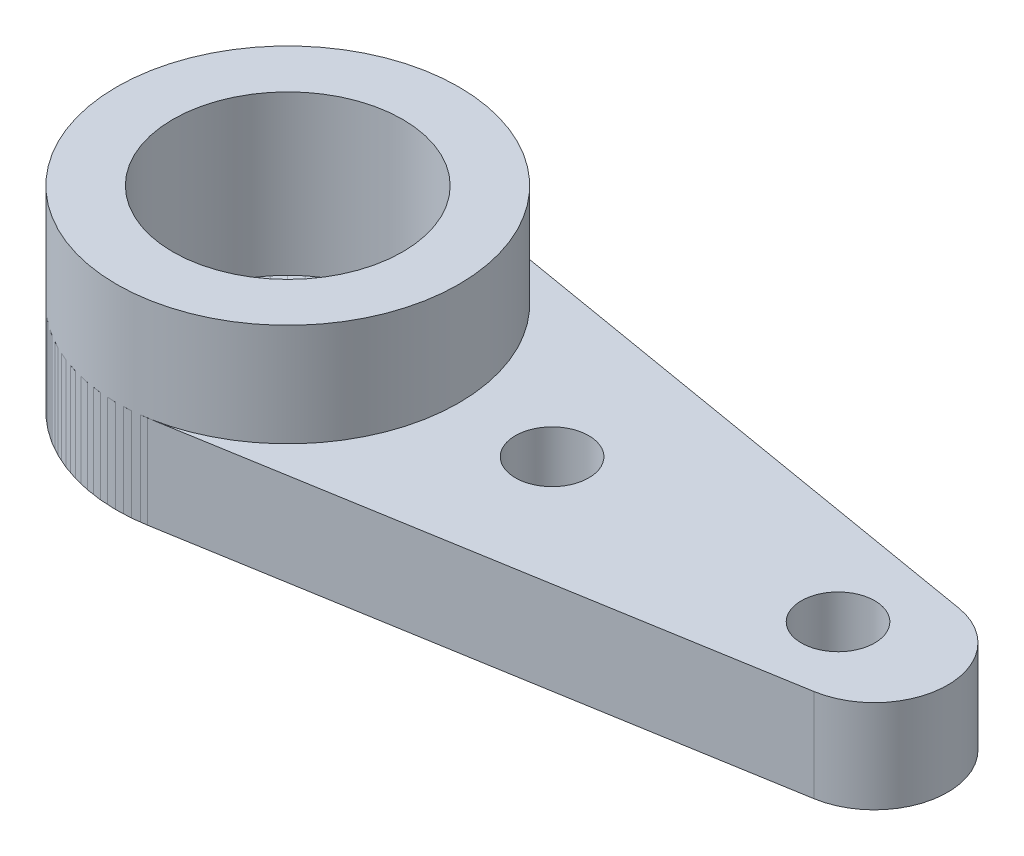
SolidWorks part; units mm, degrees
ref_plane "Front Plane" through (0, 0, 0) normal (0, 0, 1) x (1, 0, 0)
ref_plane "Top Plane" through (0, 0, 0) normal (0, 1, 0) x (1, 0, 0)
ref_plane "Right Plane" through (0, 0, 0) normal (1, 0, 0) x (0, 0, -1)
sketch "Sketch1" plane through (0, 0, 0) normal (0, 1, 0) x (1, 0, 0)
  circle A0 centre (0, 0) radius 3.5
  circle A1 centre (0, 0) radius 1.5
extrude "Boss-Extrude1" add sketch "Sketch1" along normal blind 4
sketch "Sketch2" plane through (0, 0, 0) normal (0, -1, 0) x (1, 0, 0)
  line L0 (-3.5, 0) -> (-3.5, 10.8846) construction
  line L1 (13.5, 0) -> (13.5, 8.8292) construction
  line L2 (0.5833, 3.451) -> (12.25, 1.479)
  line L3 (0, 0) -> (7.4207, 0) construction
  line L4 (0.5833, -3.451) -> (12.25, -1.479)
  arc A0 (0.5833, 3.451) -> (0.5833, -3.451) centre (0, 0) ccw
  arc A1 (12.25, -1.479) -> (12.25, 1.479) centre (12, 0) ccw
  circle A2 centre (0, 0) radius 1.5
  dimension "D1" = 17
extrude "Boss-Extrude2" add sketch "Sketch2" against normal blind 1.9 separate body
sketch "Sketch3" plane through (0, 4, 0) normal (0, 1, 0) x (1, 0, 0)
  circle A0 centre (0, 0) radius 2.35
extrude "Cut-Extrude1" cut sketch "Sketch3" against normal blind 3.25
sketch "Sketch5" plane through (0, 0, 0) normal (0, -1, 0) x (1, 0, 0)
  circle A0 centre (11.2576, 0) radius 0.75
  circle A1 centre (5.4076, 0) radius 0.75
  dimension "D1" = 5.85
extrude "Cut-Extrude2" cut sketch "Sketch5" against normal through all
